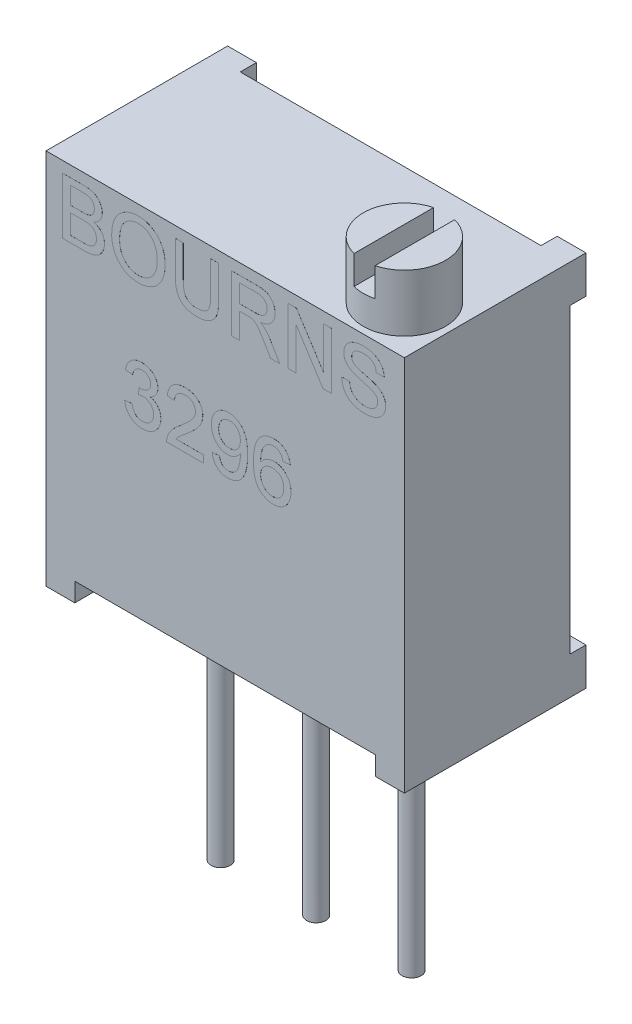
SolidWorks part; units mm, degrees
ref_plane "Plane1" through (0, 0, 0) normal (0, 0, 1) x (1, 0, 0)
ref_plane "Plane2" through (0, 0, 0) normal (0, 1, 0) x (1, 0, 0)
ref_plane "Plane3" through (0, 0, 0) normal (1, 0, 0) x (0, 0, -1)
sketch "Sketch1" plane through (0, 0, 0) normal (0, 0, 1) x (1, 0, 0)
  line L1 (-4.765, 0) -> (4.765, 0)
  line L2 (-4.765, 0) -> (-4.765, 10.03)
  line L3 (-4.765, 10.03) -> (4.765, 10.03)
  line L4 (4.765, 0) -> (4.765, 10.03)
  dimension "D1" = 9.53
  dimension "D2" = 10.03
extrude "Extrude1" add sketch "Sketch1" along normal blind 4.4
sketch "Sketch2" plane through (0, 0, 4.4) normal (0, 0, 1) x (1, 0, 0)
  line L0 (-4.765, 0) -> (4.765, 0) construction
  line L1 (-4, 0) -> (4, 0)
  line L2 (-4, 0) -> (-4, 0.5)
  line L3 (-4, 0.5) -> (4, 0.5)
  line L4 (4, 0) -> (4, 0.5)
  dimension "D1" = 8
  dimension "D2" = 0.5
extrude "Cut-Extrude1" cut sketch "Sketch2" against normal through all
sketch "Sketch3" plane through (0, 0, 0) normal (0, 0, -1) x (-1, 0, 0)
  line L1 (-4.765, 0) -> (-4, 0)
  line L2 (-4.765, 0) -> (-4.765, 1)
  line L3 (-4.765, 1) -> (-4, 1)
  line L4 (-4, 0) -> (-4, 1)
  line L5 (4.765, 0) -> (4, 0)
  line L6 (4.765, 0) -> (4.765, 1)
  line L7 (4.765, 1) -> (4, 1)
  line L8 (4, 0) -> (4, 1)
  line L9 (4.765, 10.03) -> (4, 10.03)
  line L10 (4.765, 10.03) -> (4.765, 9.03)
  line L11 (4.765, 9.03) -> (4, 9.03)
  line L12 (4, 10.03) -> (4, 9.03)
  line L13 (-4.765, 10.03) -> (-4, 10.03)
  line L14 (-4.765, 10.03) -> (-4.765, 9.03)
  line L15 (-4.765, 9.03) -> (-4, 9.03)
  line L16 (-4, 10.03) -> (-4, 9.03)
  dimension "D1" = 1
  dimension "D2" = 1
extrude "Extrude2" add sketch "Sketch3" along normal blind 0.43
sketch "Sketch4" plane through (0, 0.5, 0) normal (0, -1, 0) x (1, 0, 0)
  line L0 (0, 0) -> (0, 1.98) construction
  line L1 (-2.54, 1.98) -> (2.54, 1.98) construction
  line L2 (4.765, -0.43) -> (4, -0.43) construction
  circle A0 centre (2.54, 1.98) radius 0.255
  circle A1 centre (0, 1.98) radius 0.255
  circle A2 centre (-2.54, 1.98) radius 0.255
  dimension "D4" = 0.51
  dimension "D1" = 2.41
  dimension "D2" = 2.54
  dimension "D3" = 2.54
extrude "Extrude3" add sketch "Sketch4" along normal blind 6.9
sketch "Sketch5" plane through (0, 10.03, 0) normal (0, 1, 0) x (-1, 0, 0)
  line L0 (-4.765, 4.4) -> (4.765, 4.4) construction
  line L1 (-4.765, 4.4) -> (-4.765, -0.43) construction
  circle A0 centre (-3.495, 3.13) radius 1.095
  dimension "D3" = 2.19
  dimension "D1" = 1.27
  dimension "D2" = 1.27
extrude "Extrude4" add sketch "Sketch5" along normal blind 1.52
sketch "Sketch6" plane through (0, 11.55, 0) normal (0, 1, 0) x (-1, 0, 0)
  line L0 (-3.495, 3.13) -> (-3.495, 1.593) construction
  line L1 (-3.215, 1.593) -> (-3.775, 1.593)
  line L2 (-3.215, 1.593) -> (-3.215, 4.7702)
  line L3 (-3.215, 4.7702) -> (-3.775, 4.7702)
  line L4 (-3.775, 1.593) -> (-3.775, 4.7702)
  dimension "D1" = 0.56
extrude "Cut-Extrude2" cut sketch "Sketch6" against normal blind 0.76
sketch "Sketch7" plane through (0, 0, 4.4) normal (0, 0, 1) x (1, 0, 0)
  text T0 "BOURNS\r\n   3296" font "Arial" height 1.5
extrude "Extrude5" add sketch "Sketch7" along normal blind 0.001
